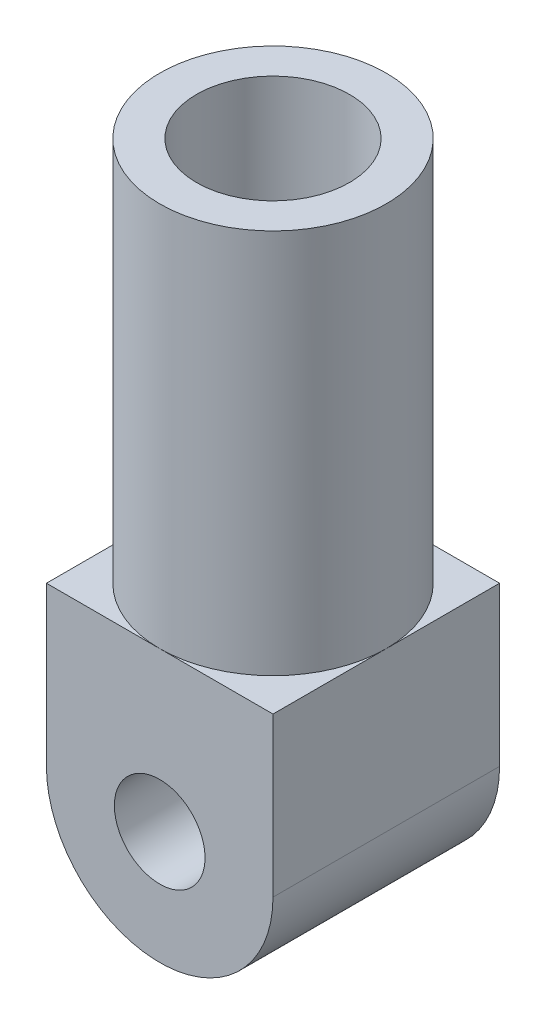
SolidWorks part; units mm, degrees
ref_plane "Front Plane" through (0, 0, 0) normal (0, 0, 1) x (1, 0, 0)
ref_plane "Top Plane" through (0, 0, 0) normal (0, 1, 0) x (1, 0, 0)
ref_plane "Right Plane" through (0, 0, 0) normal (1, 0, 0) x (0, 0, -1)
sketch "Sketch2" plane through (0, 0, 0) normal (0, 1, 0) x (1, 0, 0)
  circle A0 centre (0, 0) radius 6.75
  circle A1 centre (0, 0) radius 10
  dimension "D1" = 13.5
  dimension "D2" = 20
extrude "Boss-Extrude1" add sketch "Sketch2" against normal blind 34
sketch "Sketch3" plane through (0, -34, 0) normal (0, -1, 0) x (1, 0, 0)
  line L1 (-10, 10) -> (10, 10)
  line L2 (-10, 10) -> (-10, -10)
  line L3 (-10, -10) -> (10, -10)
  line L4 (10, 10) -> (10, -10)
  circle A0 centre (0, 0) radius 10 construction
  point P4 (0, 10)
extrude "Boss-Extrude2" add sketch "Sketch3" along normal blind 24
sketch "Sketch4" plane through (0, 0, 0) normal (0, 0, 1) x (1, 0, 0)
  line L0 (-10, -58) -> (0, -58)
  line L1 (10, -58) -> (-10, -58) construction
  line L2 (0, -58) -> (0, -40.9371) construction
  line L3 (-10, -58) -> (-10, -34) construction
  line L4 (-10, -58) -> (-10, -48)
  arc A0 (-10, -48) -> (0, -58) centre (0, -48) ccw
extrude "Cut-Extrude1" cut sketch "Sketch4" against normal blind 24 and the other way blind 24
mirror "Mirror1" about plane through (0, 0, 0) normal (1, 0, 0) of "Cut-Extrude1"
sketch "Sketch5" plane through (0, 0, -10) normal (0, 0, -1) x (-1, 0, 0)
  line L0 (-10, -48) -> (10, -48) construction
  arc A0 (-10, -48) -> (10, -48) centre (0, -48) ccw construction
  circle A1 centre (0, -48) radius 4
  dimension "D1" = 8
extrude "Cut-Extrude2" cut sketch "Sketch5" against normal through all
